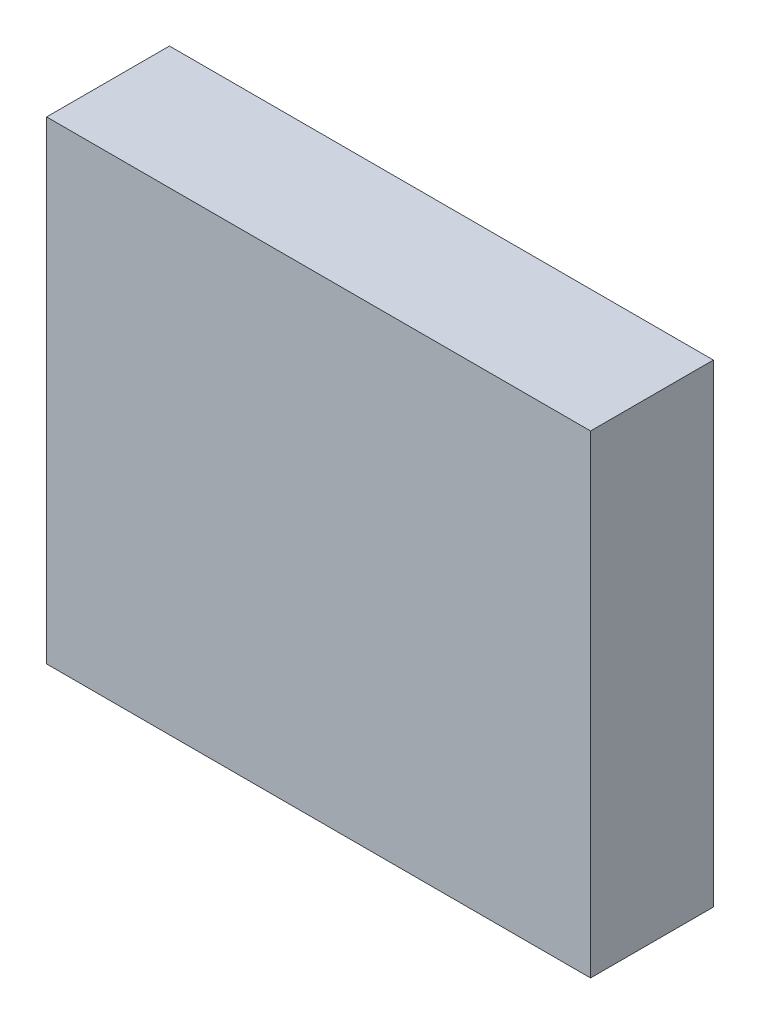
SolidWorks part; units mm, degrees
material "Custom Plastic"
ref_plane "Front Plane" through (0, 0, 0) normal (0, 0, 1) x (1, 0, 0)
ref_plane "Top Plane" through (0, 0, 0) normal (0, 1, 0) x (1, 0, 0)
ref_plane "Right Plane" through (0, 0, 0) normal (1, 0, 0) x (0, 0, -1)
sketch "Sketch1" plane through (0, 0, 0) normal (0, 0, 1) x (1, 0, 0)
  line L1 (-155, -135) -> (155, -135)
  line L2 (-155, -135) -> (-155, 135)
  line L3 (-155, 135) -> (155, 135)
  line L4 (155, -135) -> (155, 135)
  line L5 (-155, -135) -> (155, 135) construction
  line L6 (-155, 135) -> (155, -135) construction
  point P0 (0, 0)
extrude "Boss-Extrude1" add sketch "Sketch1" along normal blind 70
